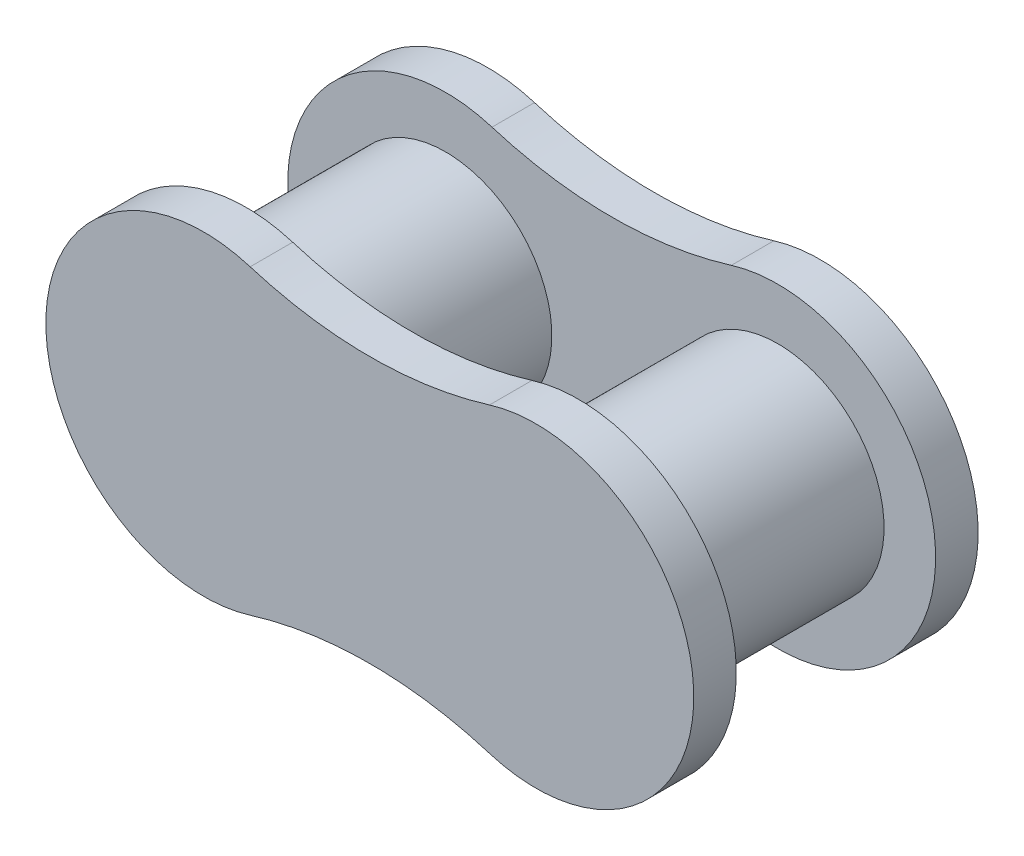
SolidWorks part; units mm, degrees
material "AISI 316 Annealed Stainless Steel Bar (SS)"
ref_plane "Front Plane" through (0, 0, 0) normal (0, 0, 1) x (1, 0, 0)
ref_plane "Top Plane" through (0, 0, 0) normal (0, 1, 0) x (1, 0, 0)
ref_plane "Right Plane" through (0, 0, 0) normal (1, 0, 0) x (0, 0, -1)
sketch "Sketch2" plane through (0, 0, 0) normal (0, 0, 1) x (1, 0, 0)
  line L0 (0, 22.0497) -> (0, -22.0497) construction
  line L1 (-35.0533, 0) -> (35.0533, 0) construction
  arc A0 (-5.7185, 7.2101) -> (-5.7185, -7.2101) centre (-7.9375, 0) ccw
  arc A3 (5.7185, 7.2101) -> (5.7185, -7.2101) centre (7.9375, 0) cw
  arc A4 (-5.7185, 7.2101) -> (5.7185, 7.2101) centre (0, 25.7911) ccw
  arc A5 (-5.7185, -7.2101) -> (5.7185, -7.2101) centre (0, -25.7911) cw
  point P3 (0, 6.35)
  point P4 (0, 0)
  point P8 (0, 0)
  dimension "D1" = 15.0876
  dimension "D3" = 7.9375
  dimension "D4" = 6.35
extrude "Boss-Extrude1" add sketch "Sketch2" along normal blind 2.032
sketch "Sketch4" plane through (0, 0, 2.032) normal (0, 0, 1) x (1, 0, 0)
  line L0 (0, 0) -> (0, -9.647) construction
  circle A0 centre (-7.9375, 0) radius 5.08
  circle A1 centre (7.9375, 0) radius 5.08
  dimension "D1" = 10.16
  dimension "D2" = 7.9375
extrude "Boss-Extrude2" add sketch "Sketch4" along normal blind 9.525
ref_plane "Plane1" through (0, 0, 6.7945) normal (0, 0, 1) x (1, 0, 0)
mirror "Mirror1" about plane through (0, 0, 6.7945) normal (0, 0, 1) of "Boss-Extrude1"
ref_plane "Plane2" through (0, 0, -2.032) normal (0, 0, -1) x (-1, 0, 0)
